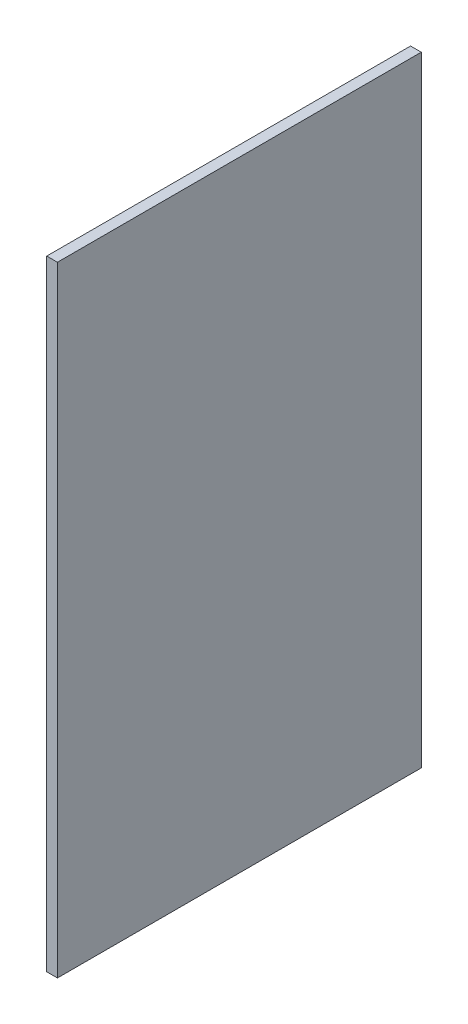
SolidWorks part; units mm, degrees
ref_plane "Front" through (0, 0, 0) normal (0, 0, 1) x (1, 0, 0)
ref_plane "Top" through (0, 0, 0) normal (0, 1, 0) x (1, 0, 0)
ref_plane "Right" through (0, 0, 0) normal (1, 0, 0) x (0, 0, -1)
sketch "Sketch1" plane through (0, 0, 0) normal (1, 0, 0) x (0, 0, -1)
  line L1 (-54, 92) -> (54, 92)
  line L2 (-54, 92) -> (-54, -92)
  line L3 (-54, -92) -> (54, -92)
  line L4 (54, 92) -> (54, -92)
  line L5 (-54, 92) -> (54, -92) construction
  line L6 (-54, -92) -> (54, 92) construction
  point P0 (0, 0)
  dimension "D1" = 108
  dimension "D2" = 184
extrude "Boss-Extrude1" add sketch "Sketch1" along normal blind 3.175
